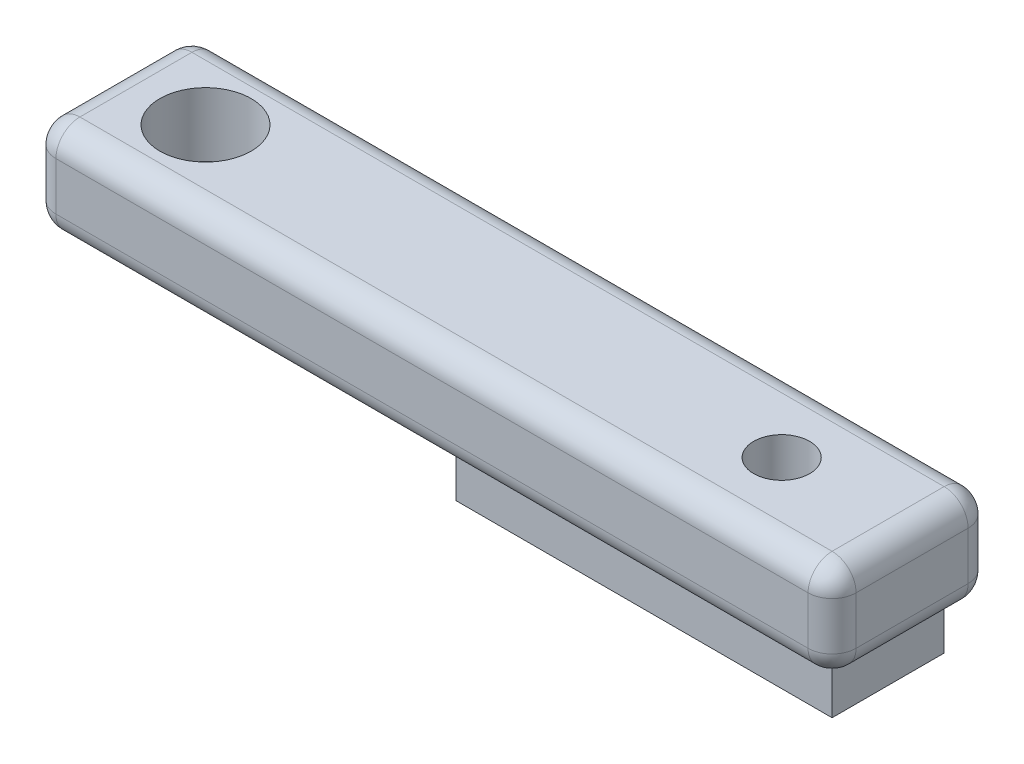
SolidWorks part; units mm, degrees
ref_plane "Front Plane" through (0, 0, 0) normal (0, 0, 1) x (1, 0, 0)
ref_plane "Top Plane" through (0, 0, 0) normal (0, 1, 0) x (1, 0, 0)
ref_plane "Right Plane" through (0, 0, 0) normal (1, 0, 0) x (0, 0, -1)
sketch "Sketch1" plane through (0, 0, 0) normal (0, 1, 0) x (1, 0, 0)
  line L1 (-25, 5) -> (25, 5)
  line L2 (-25, 5) -> (-25, -5)
  line L3 (-25, -5) -> (25, -5)
  line L4 (25, 5) -> (25, -5)
  line L5 (-25, 5) -> (25, -5) construction
  line L6 (-25, -5) -> (25, 5) construction
  point P0 (0, 0)
  dimension "D1" = 50
  dimension "D2" = 10
extrude "Boss-Extrude1" add sketch "Sketch1" along normal blind 6
sketch "Sketch2" plane through (0, 6, 0) normal (0, 1, 0) x (1, 0, 0)
  line L1 (-25, 5) -> (-25, -5) construction
  circle A0 centre (-19.15, 0) radius 2.85
  circle A1 centre (16.85, 0) radius 1.5
  dimension "D1" = 5.7
  dimension "D2" = 3
  dimension "D3" = 3
  dimension "D4" = 36
extrude "Cut-Extrude1" cut sketch "Sketch2" against normal blind 4
sketch "Sketch3" plane through (0, 2, 0) normal (0, 1, 0) x (1, 0, 0)
  circle A0 centre (16.85, 0) radius 1.5
extrude "Cut-Extrude2" cut sketch "Sketch3" against normal blind 4
fillet "Fillet1" radius 1.5 12 edges at (25, 6, 0) (25, 0, 0) (0, 6, 5) (25, 3, 5) (0, 0, 5) (-25, 6, 0) (-25, 3, 5) (-25, 0, 0) (25, 3, -5) (0, 6, -5) (-25, 3, -5) (0, 0, -5)
sketch "Sketch6" plane through (0, 0, 0) normal (0, -1, 0) x (1, 0, 0)
  line L0 (-23.5, -3.5) -> (23.5, -3.5) construction
  line L1 (23.5, 3.5) -> (0, 3.5)
  line L2 (23.5, 3.5) -> (23.5, -3.5)
  line L3 (23.5, -3.5) -> (0, -3.5)
  line L4 (0, 3.5) -> (0, -3.5)
extrude "Boss-Extrude3" add sketch "Sketch6" along normal blind 3.01
sketch "Sketch7" plane through (0, 0, 0) normal (0, 1, 0) x (1, 0, 0)
  circle A0 centre (16.85, 0) radius 1.75
  dimension "D1" = 3.5
extrude "Cut-Extrude4" cut sketch "Sketch7" against normal through all both and the other way through all
sketch "Sketch8" plane through (0, 2, 0) normal (0, 1, 0) x (1, 0, 0)
  circle A0 centre (-19.15, 0) radius 1.5
  dimension "D1" = 3
extrude "Cut-Extrude5" cut sketch "Sketch8" against normal blind 10
